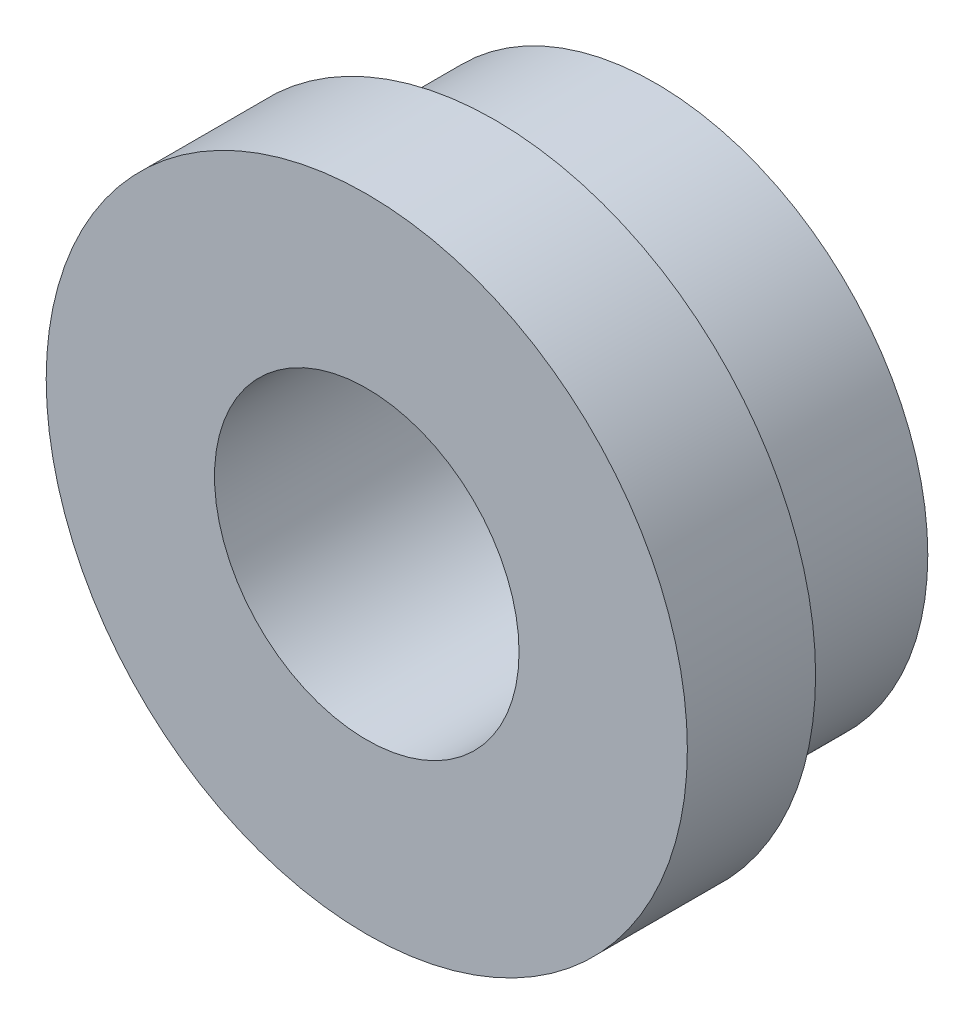
SolidWorks part; units mm, degrees
ref_plane "Front Plane" through (0, 0, 0) normal (0, 0, 1) x (1, 0, 0)
ref_plane "Top Plane" through (0, 0, 0) normal (0, 1, 0) x (1, 0, 0)
ref_plane "Right Plane" through (0, 0, 0) normal (1, 0, 0) x (0, 0, -1)
sketch "Sketch1" plane through (0, 0, 0) normal (0, 0, 1) x (1, 0, 0)
  circle A0 centre (0, 0) radius 17
  circle A1 centre (0, 0) radius 9.5
  dimension "D1" = 19
  dimension "D2" = 34
extrude "Boss-Extrude1" add sketch "Sketch1" along normal blind 10
sketch "Sketch2" plane through (0, 0, 10) normal (0, 0, 1) x (1, 0, 0)
  circle A0 centre (0, 0) radius 20
  circle A1 centre (0, 0) radius 9.5 construction
  circle A2 centre (0, 0) radius 9.5
  dimension "D1" = 40
extrude "Boss-Extrude2" add sketch "Sketch2" along normal blind 8
chamfer "Chamfer1" distance 2 angle 45 1 edges at (9.5, 0, 0)
fillet "Fillet1" radius 2 1 edges at (9.5, 0, 2)
